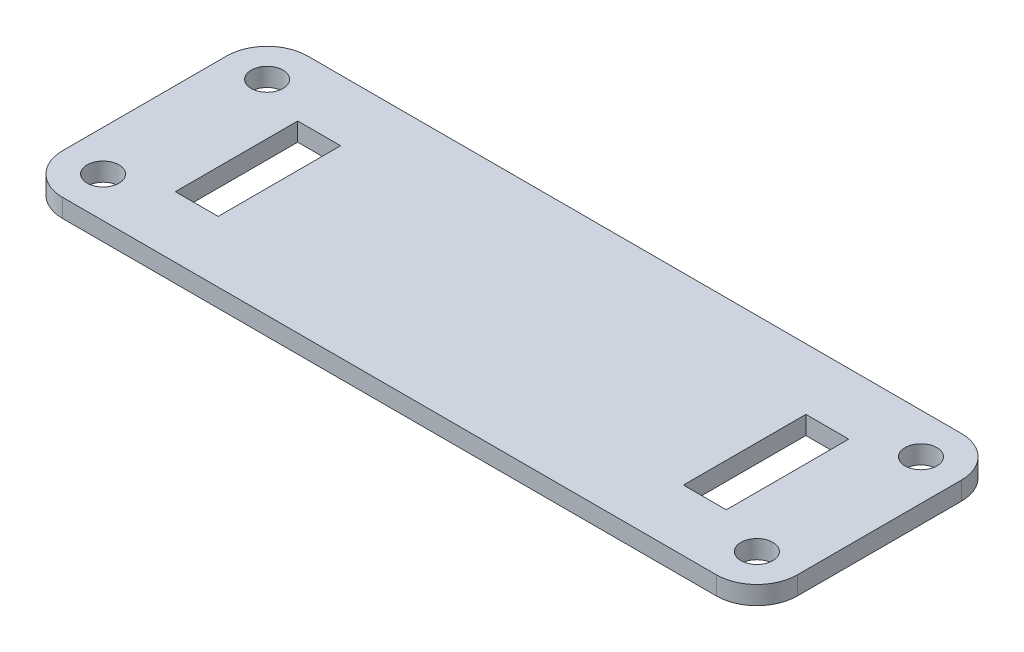
SolidWorks part; units mm, degrees
ref_plane "Front Plane" through (0, 0, 0) normal (0, 0, 1) x (1, 0, 0)
ref_plane "Top Plane" through (0, 0, 0) normal (0, 1, 0) x (1, 0, 0)
ref_plane "Right Plane" through (0, 0, 0) normal (1, 0, 0) x (0, 0, -1)
sketch "Sketch1" plane through (0, 0, 0) normal (0, 1, 0) x (1, 0, 0)
  line L0 (-56.93, 18.9767) -> (-47.23, 15.7433) construction
  line L1 (-53.4, -20) -> (53.4, -20)
  line L2 (-60, -13.4) -> (-60, 13.4)
  line L3 (-53.4, 20) -> (53.4, 20)
  line L4 (60, -13.4) -> (60, 13.4)
  line L5 (-47.23, -15.7433) -> (47.23, 15.7433) construction
  line L6 (-60, 20) -> (-56.93, 18.9767) construction
  line L7 (-47.23, 15.7433) -> (0, 0) construction
  line L8 (-60, 13.4) -> (-60, 20) construction
  line L9 (-60, 20) -> (-53.4, 20) construction
  line L10 (0, 20) -> (0, 0) construction
  line L11 (-60, 0) -> (60, 0) construction
  line L12 (60, 20) -> (53.4, 20) construction
  line L13 (60, 13.4) -> (60, 20) construction
  line L14 (60, 20) -> (56.93, 18.9767) construction
  line L15 (56.93, 18.9767) -> (47.23, 15.7433) construction
  line L16 (53.4, 20) -> (60, 20) construction
  line L17 (56.93, 18.9767) -> (60, 20) construction
  line L18 (60, 13.4) -> (60, 20) construction
  line L19 (47.23, 15.7433) -> (56.93, 18.9767) construction
  line L20 (47.23, -15.7433) -> (56.93, -18.9767) construction
  line L21 (60, -13.4) -> (60, -20) construction
  line L22 (56.93, -18.9767) -> (60, -20) construction
  line L23 (53.4, -20) -> (60, -20) construction
  line L24 (56.93, -18.9767) -> (47.23, -15.7433) construction
  line L25 (60, -20) -> (56.93, -18.9767) construction
  line L26 (60, -13.4) -> (60, -20) construction
  line L27 (60, -20) -> (53.4, -20) construction
  line L28 (-60, -20) -> (-53.4, -20) construction
  line L29 (-60, -13.4) -> (-60, -20) construction
  line L30 (-60, -20) -> (-56.93, -18.9767) construction
  line L31 (-56.93, -18.9767) -> (-47.23, -15.7433) construction
  line L32 (-60, -20) -> (-60, -13.4) construction
  line L33 (-60, -20) -> (-56.93, -18.9767) construction
  line L34 (-60, -20) -> (-53.4, -20) construction
  line L35 (60, -20) -> (60, -13.4) construction
  line L36 (56.93, -18.9767) -> (60, -20) construction
  line L37 (53.4, -20) -> (60, -20) construction
  line L38 (47.23, -15.7433) -> (56.93, -18.9767) construction
  line L39 (0, 0) -> (47.23, -15.7433) construction
  line L40 (0, 0) -> (0, -20) construction
  line L41 (-56.93, -18.9767) -> (-47.23, -15.7433) construction
  arc A0 (-53.4, 20) -> (-60, 13.4) centre (-53.4, 13.4) ccw
  circle A1 centre (-53.4, 13.4) radius 2.6
  arc A2 (-60, 13.4) -> (-47.23, 15.7433) centre (-53.4, 13.4) ccw construction
  arc A3 (-47.23, 15.7433) -> (-53.4, 20) centre (-53.4, 13.4) ccw construction
  arc A4 (47.23, 15.7433) -> (53.4, 20) centre (53.4, 13.4) cw construction
  arc A5 (60, 13.4) -> (47.23, 15.7433) centre (53.4, 13.4) cw construction
  circle A6 centre (53.4, 13.4) radius 2.6
  arc A7 (53.4, 20) -> (60, 13.4) centre (53.4, 13.4) cw
  arc A8 (60, -13.4) -> (47.23, -15.7433) centre (53.4, -13.4) ccw construction
  arc A9 (47.23, -15.7433) -> (53.4, -20) centre (53.4, -13.4) ccw construction
  arc A10 (-47.23, -15.7433) -> (-53.4, -20) centre (-53.4, -13.4) cw construction
  arc A11 (-60, -13.4) -> (-47.23, -15.7433) centre (-53.4, -13.4) cw construction
  arc A12 (53.4, -20) -> (60, -13.4) centre (53.4, -13.4) ccw
  circle A13 centre (53.4, -13.4) radius 2.6
  circle A14 centre (-53.4, -13.4) radius 2.6
  arc A15 (-53.4, -20) -> (-60, -13.4) centre (-53.4, -13.4) cw
  point P0 (0, 0)
  point P9 (-53.4, 16)
  point P10 (-53.4, 20)
  point P24 (53.4, 20)
  point P25 (53.4, 16)
  point P26 (50, 0)
  point P27 (-50, 0)
  point P40 (53.4, -16)
  point P41 (53.4, -20)
  point P42 (-53.4, -20)
  point P43 (-53.4, -16)
  dimension "D3" = 5.2
  dimension "D1" = 120
  dimension "D2" = 40
  dimension "D4" = 4
extrude "Boss-Extrude1" add sketch "Sketch1" along normal mid plane 3
sketch "Sketch2" plane through (0, 1.5, 0) normal (0, 1, 0) x (1, 0, 0)
  line L0 (0, 20) -> (0, -20) construction
  line L1 (-45, 10) -> (-38, 10)
  line L2 (-45, 10) -> (-45, -10)
  line L3 (-45, -10) -> (-38, -10)
  line L4 (-38, 10) -> (-38, -10)
  line L5 (53.4, 20) -> (-53.4, 20) construction
  line L6 (-53.4, -20) -> (53.4, -20) construction
  line L7 (-60, 13.4) -> (-60, -13.4) construction
  line L8 (38, 10) -> (38, -10)
  line L9 (45, -10) -> (38, -10)
  line L10 (45, 10) -> (45, -10)
  line L11 (45, 10) -> (38, 10)
  point P12 (-38, 0)
  dimension "D1" = 15
  dimension "D2" = 7
  dimension "D3" = 20
extrude "Cut-Extrude1" cut sketch "Sketch2" against normal through all
